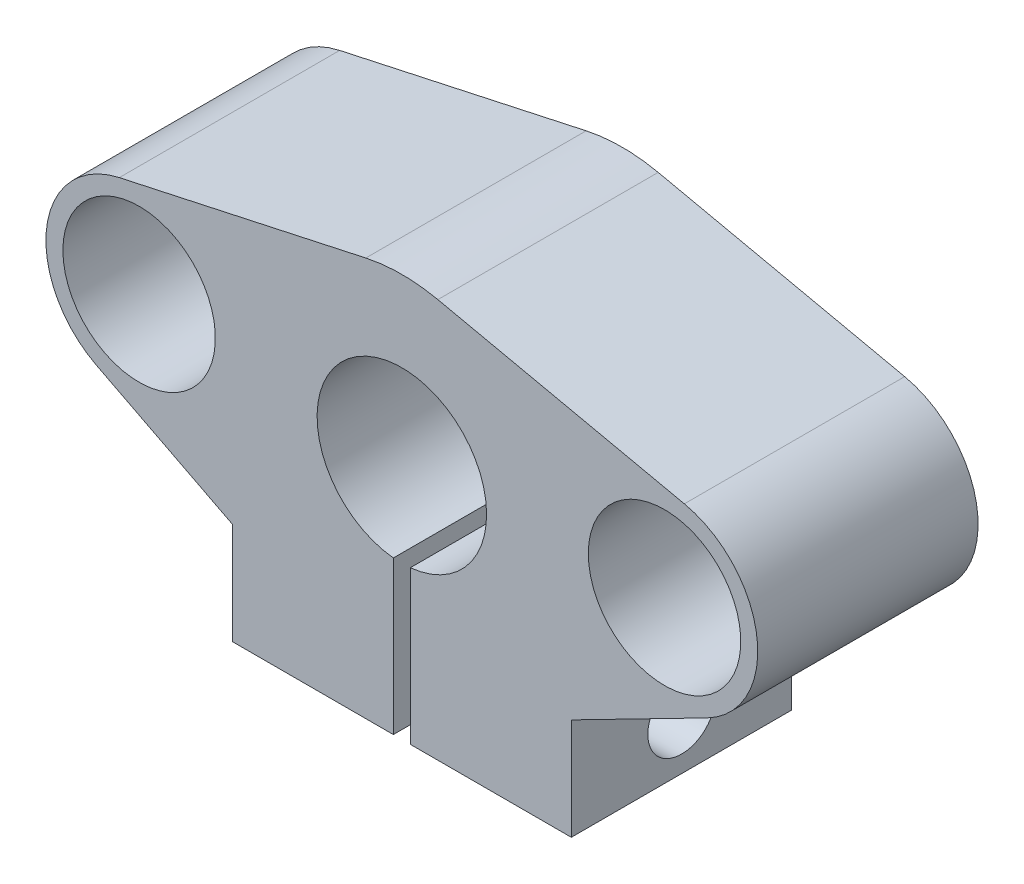
SolidWorks part; units mm, degrees
ref_plane "前视基准面" through (0, 0, 0) normal (0, 0, 1) x (1, 0, 0)
ref_plane "上视基准面" through (0, 0, 0) normal (0, 1, 0) x (1, 0, 0)
ref_plane "右视基准面" through (0, 0, 0) normal (1, 0, 0) x (0, 0, -1)
sketch "草图1" plane through (0, 0, 0) normal (0, 0, 1) x (1, 0, 0)
  line L0 (0, 0) -> (0, 50000) construction
  line L1 (0, 0) -> (50000, 0) construction
  line L2 (15.5, 3) -> (31.2948, 18.7948)
  line L3 (-21, 12) -> (21, 12)
  line L4 (-21, 12) -> (-21, -12)
  line L5 (-21, -12) -> (21, -12)
  line L6 (21, 12) -> (21, -12)
  line L7 (-10, -12) -> (10, -12)
  line L8 (-10, -12) -> (-10, -6)
  line L9 (-10, -6) -> (10, -6)
  line L10 (10, -12) -> (10, -6)
  line L11 (15.5, 3) -> (31.7304, -13.2304)
  line L12 (-15.5, 3) -> (-31.7304, -13.2304)
  line L13 (-15.5, 3) -> (-31.2948, 18.7948)
  line L14 (0, 12) -> (-21, 7.4323)
  line L15 (-10, -6) -> (-21, -0.3611)
  line L16 (10, -6) -> (21, -0.3611)
  line L17 (0, 12) -> (21, 7.4323)
  circle A0 centre (15.5, 3) radius 4.4985
  circle A1 centre (-15.5, 3) radius 4.4985
  circle A2 centre (0, 2) radius 5
  circle A3 centre (15.5, 3) radius 5.5
  circle A4 centre (-15.5, 3) radius 5.5
  dimension "D1" = 15
  dimension "D5" = 14
  dimension "D2" = 42
  dimension "D3" = 24
  dimension "D4" = 5.5
extrude "凸台-拉伸1" add sketch "草图1" along normal blind 13 contours A4 L15 L9 L16 A3 L17 L14 A2 | L13 A4 L12 A1 | A4 L13 A1 L12 | L2 A3 L11 A0 | A3 L2 A0 L11 | L5 L10 L9 L8
sketch "草图2" plane through (-10, 0, 0) normal (-1, 0, 0) x (0, 0, 1)
  line L0 (0, -9) -> (50000, -9) construction
  line L1 (0, -12) -> (0, -6) construction
  line L2 (6.5, -12) -> (6.5, 49988) construction
  line L3 (13, -12) -> (0, -12) construction
  circle A0 centre (6.4879, -9) radius 2
  point P4 (0, -9)
  point P9 (6.5, -12)
extrude "切除-拉伸1" cut sketch "草图2" against normal through all
sketch "草图3" plane through (0, -12, 0) normal (0, -1, 0) x (1, 0, 0)
  line L0 (0, 0) -> (0, 50000) construction
  line L1 (-10, 6.5) -> (49990, 6.5) construction
  line L2 (-10, 13) -> (-10, 0) construction
  line L3 (-10, 13) -> (10, 13) construction
  line L4 (-0.5, 13) -> (0.5, 13)
  line L5 (-0.5, 13) -> (-0.5, 0)
  line L6 (-0.5, 0) -> (0.5, 0)
  line L7 (0.5, 13) -> (0.5, 0)
  line L8 (-10, 0) -> (10, 0) construction
  point P7 (-10, 6.5)
extrude "切除-拉伸2" cut sketch "草图3" against normal blind 13
fillet "圆角1" radius 10 1 edges at (0, 12, 6.5)
